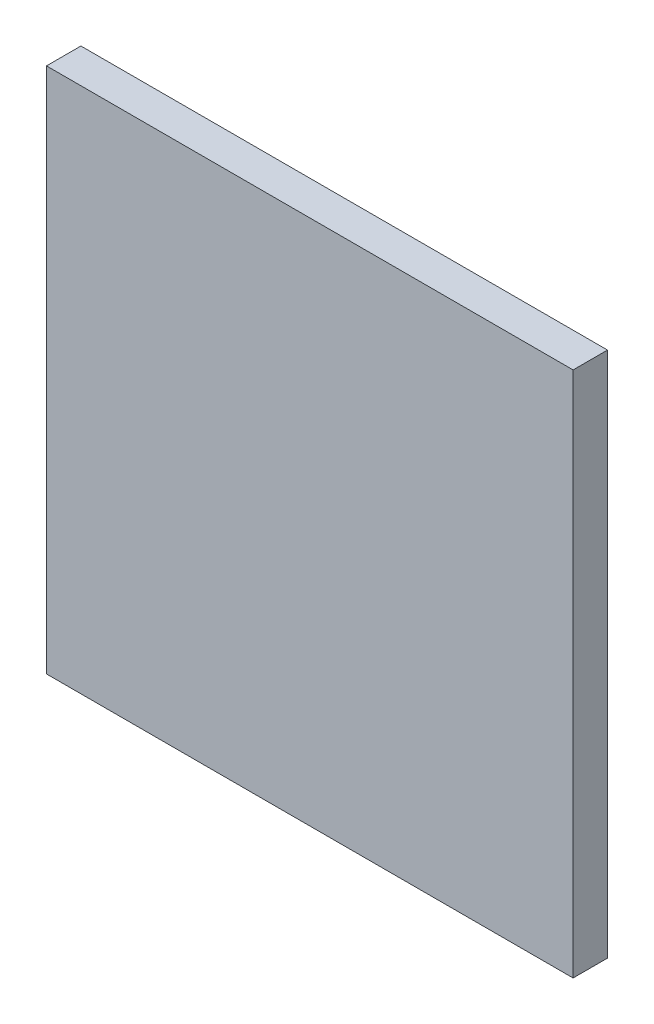
SolidWorks part; units mm, degrees
ref_plane "Front Plane" through (0, 0, 0) normal (0, 0, 1) x (1, 0, 0)
ref_plane "Top Plane" through (0, 0, 0) normal (0, 1, 0) x (1, 0, 0)
ref_plane "Right Plane" through (0, 0, 0) normal (1, 0, 0) x (0, 0, -1)
sketch "Sketch1" plane through (0, 0, 0) normal (0, 0, 1) x (1, 0, 0)
  line L1 (-33.0039, 34.9921) -> (67.9961, 34.9921)
  line L2 (-33.0039, 34.9921) -> (-33.0039, -66.0079)
  line L3 (-33.0039, -66.0079) -> (67.9961, -66.0079)
  line L4 (67.9961, 34.9921) -> (67.9961, -66.0079)
  point P4 (0, 0)
  dimension "D1" = 101
  dimension "D2" = 101
extrude "Boss-Extrude1" add sketch "Sketch1" along normal blind 6.6
